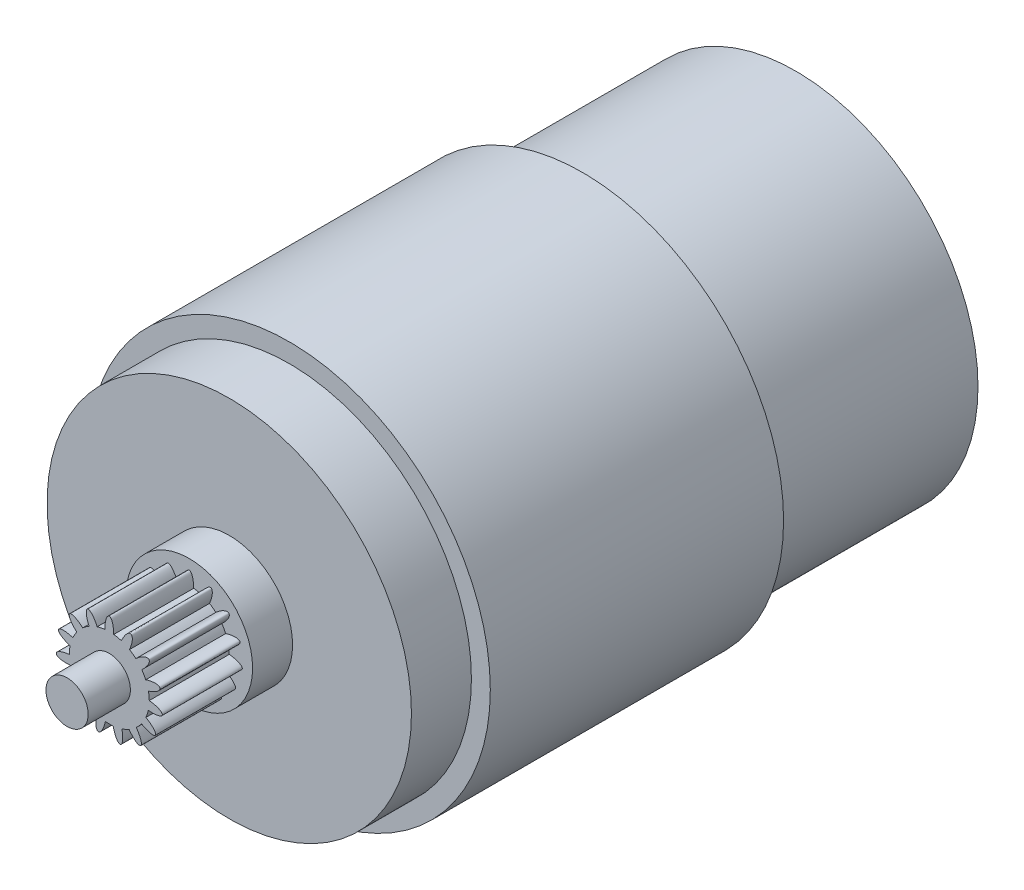
SolidWorks part; units mm, degrees
ref_plane "Front Plane" through (0, 0, 0) normal (0, 0, 1) x (1, 0, 0)
ref_plane "Top Plane" through (0, 0, 0) normal (0, 1, 0) x (1, 0, 0)
ref_plane "Right Plane" through (0, 0, 0) normal (1, 0, 0) x (0, 0, -1)
sketch "Sketch1" plane through (0, 0, 0) normal (0, 0, 1) x (1, 0, 0)
  circle A0 centre (0, 0) radius 22.987
  dimension "D1" = 45.974
extrude "Boss-Extrude1" add sketch "Sketch1" along normal mid plane 33.528
sketch "Sketch2" plane through (0, 0, -16.764) normal (0, 0, -1) x (-1, 0, 0)
  circle A0 centre (0, 0) radius 20.828
  dimension "D1" = 41.656
extrude "Boss-Extrude2" add sketch "Sketch2" along normal blind 24.384
sketch "Sketch3" plane through (0, 0, -41.148) normal (0, 0, -1) x (-1, 0, 0)
  circle A0 centre (0, 0) radius 7.366
  dimension "D1" = 14.732
extrude "Boss-Extrude3" add sketch "Sketch3" along normal blind 4.318
sketch "Sketch4" plane through (0, 0, 16.764) normal (0, 0, 1) x (1, 0, 0)
  circle A0 centre (0, 0) radius 20.828
  dimension "D1" = 41.656
extrude "Boss-Extrude4" add sketch "Sketch4" along normal blind 6.858
sketch "Sketch5" plane through (0, 0, 23.622) normal (0, 0, 1) x (1, 0, 0)
  circle A0 centre (0, 0) radius 7.239
  dimension "D1" = 14.478
extrude "Boss-Extrude5" add sketch "Sketch5" along normal blind 4.572
sketch "Sketch6" plane through (0, 0, 28.194) normal (0, 0, 1) x (1, 0, 0)
  circle A0 centre (0, 0) radius 2.413
  dimension "D1" = 4.826
extrude "Boss-Extrude6" add sketch "Sketch6" along normal blind 13.97
sketch "Sketch7" plane through (0, 0, 28.194) normal (0, 0, 1) x (1, 0, 0)
  circle A0 centre (0, 0) radius 4.572
  dimension "D1" = 9.144
extrude "Boss-Extrude7" add sketch "Sketch7" along normal offset from surface (9.144 mm away) 4.826 up to face at (2.413, 0, 42.164)
sketch "Sketch8" plane through (0, 0, 28.194) normal (0, 0, 1) x (1, 0, 0)
  line L0 (0, -25.2857) -> (0, 25.2857) construction
  circle A0 centre (0, 0) radius 4.572 construction
  ellipse E0 centre (0, 4.572) end of major axis (0, 6.096) minor radius 0.508
  dimension "D1" = 1.016
  dimension "D2" = 1.524
extrude "Boss-Extrude8" add sketch "Sketch8" along normal up to surface (9.144 mm away) up to face at (2.413, 0, 37.338)
ref_axis "Axis1" through (0, 0, -49.8475) along (0, 0, 1)
pattern_circular "CirPattern1" count 15 over 360 about axis through (0, 0, -49.8475) along (0, 0, 1) of "Boss-Extrude8"
